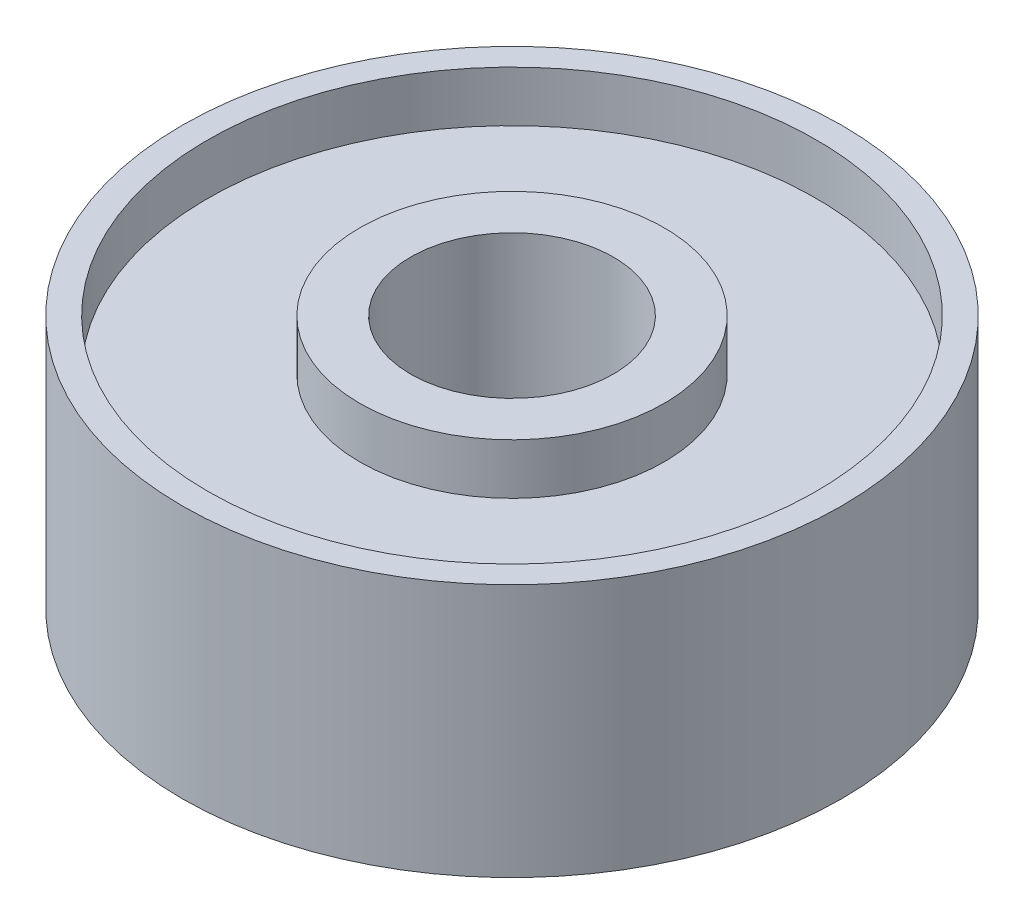
SolidWorks part; units mm, degrees
ref_plane "Спереди" through (0, 0, 0) normal (0, 0, 1) x (1, 0, 0)
ref_plane "Сверху" through (0, 0, 0) normal (0, 1, 0) x (1, 0, 0)
ref_plane "Справа" through (0, 0, 0) normal (1, 0, 0) x (0, 0, -1)
sketch "Эскиз1" plane through (0, 0, 0) normal (0, 1, 0) x (1, 0, 0)
  circle A0 centre (0, 0) radius 2
  circle A1 centre (0, 0) radius 6.5
  dimension "D1" = 13
  dimension "D2" = 4
extrude "Бобышка-Вытянуть1" add sketch "Эскиз1" along normal blind 5
sketch "Эскиз2" plane through (0, 5, 0) normal (0, 1, 0) x (1, 0, 0)
  circle A0 centre (0, 0) radius 3
  circle A1 centre (0, 0) radius 6
  dimension "D1" = 6
  dimension "D2" = 12
extrude "Вырез-Вытянуть1" cut sketch "Эскиз2" against normal blind 1
sketch "Эскиз3" plane through (0, 0, 0) normal (0, -1, 0) x (1, 0, 0)
  circle A0 centre (0, 0) radius 3
  circle A1 centre (0, 0) radius 6
  dimension "D1" = 6
  dimension "D2" = 12
extrude "Вырез-Вытянуть2" cut sketch "Эскиз3" against normal blind 1
